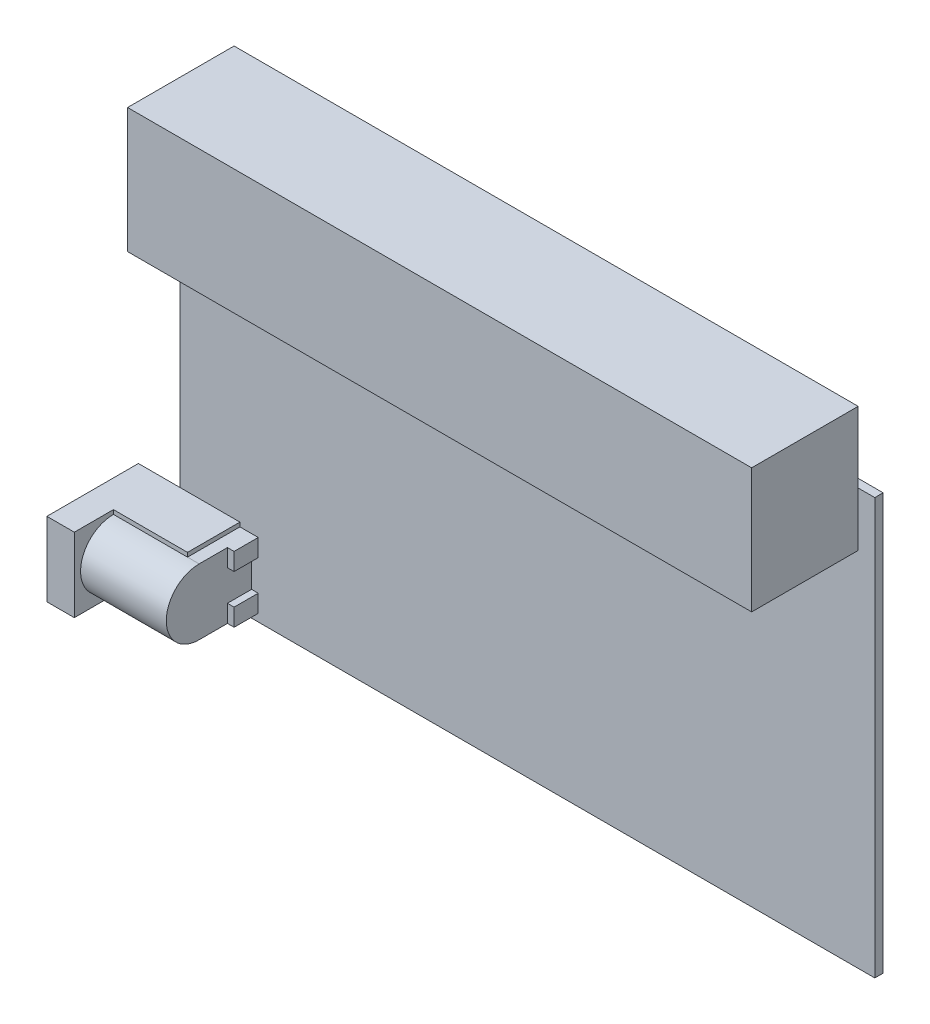
SolidWorks part; units mm, degrees
ref_plane "Front Plane" through (0, 0, 0) normal (0, 0, 1) x (1, 0, 0)
ref_plane "Top Plane" through (0, 0, 0) normal (0, 1, 0) x (1, 0, 0)
ref_plane "Right Plane" through (0, 0, 0) normal (1, 0, 0) x (0, 0, -1)
sketch "Sketch1" plane through (0, 0, 0) normal (0, 0, 1) x (1, 0, 0)
  line L1 (-41.75, 25) -> (41.75, 25)
  line L2 (-41.75, 25) -> (-41.75, -25)
  line L3 (-41.75, -25) -> (41.75, -25)
  line L4 (41.75, 25) -> (41.75, -25)
  dimension "D1" = 50
  dimension "D2" = 83.5
  dimension "D3" = 25
  dimension "D4" = 41.75
extrude "Boss-Extrude1" add sketch "Sketch1" along normal blind 1
sketch "Sketch2" plane through (0, 0, 1) normal (0, 0, 1) x (1, 0, 0)
  line L1 (-35.25, 33.5) -> (39.75, 33.5)
  line L2 (-35.25, 33.5) -> (-35.25, 18.5)
  line L3 (-35.25, 18.5) -> (39.75, 18.5)
  line L4 (39.75, 33.5) -> (39.75, 18.5)
  line L5 (41.75, 25) -> (-41.75, 25) construction
  line L6 (-41.75, 25) -> (-41.75, -25) construction
  dimension "D1" = 15
  dimension "D2" = 6.5
  dimension "D3" = 75
  dimension "D4" = 6.5
extrude "Boss-Extrude2" add sketch "Sketch2" along normal blind 12.8
sketch "Sketch3" plane through (0, 0, 1) normal (0, 0, 1) x (1, 0, 0)
  line L0 (-41.75, 25) -> (-41.75, -25) construction
  line L1 (-46.75, -15.7) -> (-32.25, -15.7)
  line L2 (-46.75, -15.7) -> (-46.75, -24.6)
  line L3 (-46.75, -24.6) -> (-32.25, -24.6)
  line L4 (-32.25, -15.7) -> (-32.25, -24.6)
  line L5 (-41.75, -25) -> (41.75, -25) construction
  line L6 (-43.45, -15.7) -> (-43.45, -24.6)
  dimension "D1" = 8.9
  dimension "D2" = 14.5
  dimension "D3" = 5
  dimension "D4" = 0.4
  dimension "D5" = 3.3
extrude "Boss-Extrude3" add sketch "Sketch3" along normal blind 11 separate body contours L6 L1 L2 L3
sketch "Sketch4" plane through (-43.45, 0, 0) normal (1, 0, 0) x (0, 0, -1)
  line L0 (-1, -25) -> (-1, 25) construction
  line L1 (-7.3, -16.2) -> (-1, -16.2)
  line L3 (-7.3, -24.1) -> (-1, -24.1)
  line L4 (-1, -16.2) -> (-1, -24.1)
  line L5 (-12, -15.7) -> (-12, -24.6) construction
  arc A0 (-7.3, -24.1) -> (-7.3, -16.2) centre (-7.3, -20.15) cw
  point P9 (-12, -20.15)
  dimension "D3" = 3.95
  dimension "D1" = 6.3
  dimension "D2" = 7.9
extrude "Boss-Extrude4" add sketch "Sketch4" along normal blind 10.3
sketch "Sketch5" plane through (0, -24.1, 0) normal (0, -1, 0) x (1, 0, 0)
  line L0 (-34.55, 7.3) -> (-34.55, 1)
  line L1 (-33.15, 7.3) -> (-43.45, 7.3) construction
  line L2 (-33.15, 1) -> (-41.75, 1) construction
  line L3 (-33.15, 7.3) -> (-33.15, 1) construction
  line L9 (-43.45, 7.3) -> (-43.45, 1)
  line L10 (-43.45, 1) -> (-41.75, 1)
  line L11 (-41.75, 1) -> (-33.15, 1)
  line L12 (-33.15, 1) -> (-33.15, 7.3)
  line L13 (-33.15, 7.3) -> (-43.45, 7.3)
  line L14 (-43.45, 7.3) -> (-43.45, 1)
  line L15 (-43.45, 1) -> (-41.75, 1)
  line L16 (-41.75, 1) -> (-34.55, 1)
  line L18 (-34.55, 7.3) -> (-43.45, 7.3)
  dimension "D1" = 1.4
  dimension "D2" = 0
extrude "Boss-Extrude6" add sketch "Sketch5" along normal up to vertex
sketch "Sketch6" plane through (0, -16.2, 0) normal (0, 1, 0) x (1, 0, 0)
  line L0 (-34.55, -7.3) -> (-34.55, -1)
  line L1 (-33.15, -7.3) -> (-43.45, -7.3) construction
  line L2 (-33.15, -1) -> (-41.75, -1) construction
  line L3 (-33.15, -1) -> (-33.15, -7.3) construction
  line L9 (-43.45, -1) -> (-43.45, -7.3)
  line L10 (-43.45, -7.3) -> (-33.15, -7.3)
  line L11 (-33.15, -7.3) -> (-33.15, -1)
  line L12 (-33.15, -1) -> (-41.75, -1)
  line L13 (-41.75, -1) -> (-43.45, -1)
  line L15 (-34.55, -7.3) -> (-33.15, -7.3)
  line L16 (-33.15, -7.3) -> (-33.15, -1)
  line L17 (-33.15, -1) -> (-34.55, -1)
  line M7 (-43.45, -1) -> (-43.45, -7.3)
  line M8 (-43.45, -7.3) -> (-33.15, -7.3)
  line M10 (-33.15, -1) -> (-41.75, -1)
  line M11 (-41.75, -1) -> (-43.45, -1)
  dimension "D1" = 1.4
  dimension "D2" = 0
extrude "Boss-Extrude7" add sketch "Sketch6" along normal up to vertex contours L0 M8 M10 M11 M7
sketch "Sketch7" plane through (-33.15, 0, 0) normal (1, 0, 0) x (0, 0, -1)
  line L1 (-3.9, -22) -> (-1, -22)
  line L2 (-3.9, -22) -> (-3.9, -24.1)
  line L3 (-3.9, -24.1) -> (-1, -24.1)
  line L4 (-1, -22) -> (-1, -24.1)
  line L5 (-3.9, -18.3) -> (-1, -18.3)
  line L6 (-3.9, -18.3) -> (-3.9, -16.2)
  line L7 (-3.9, -16.2) -> (-1, -16.2)
  line L8 (-1, -18.3) -> (-1, -16.2)
  dimension "D1" = 2.9
  dimension "D2" = 2.9
  dimension "D3" = 2.1
  dimension "D4" = 2.1
extrude "Boss-Extrude8" add sketch "Sketch7" along normal blind 0.8
sketch "Sketch8" plane through (-46.75, 0, 0) normal (-1, 0, 0) x (0, 0, 1)
  circle A0 centre (7.3, -20.15) radius 2.25
  dimension "D1" = 4.5
extrude "Cut-Extrude1" cut sketch "Sketch8" against normal up to vertex (12.2 mm away)
sketch "Sketch9" plane through (-33.15, 0, 0) normal (1, 0, 0) x (0, 0, -1)
  line L1 (-1, -18.3) -> (-6.5401, -18.3)
  line L2 (-1, -22) -> (-6.5401, -22)
  arc A0 (-6.5401, -18.3) -> (-6.5401, -22) centre (-7.3, -20.15) ccw
  dimension "D1" = 2
